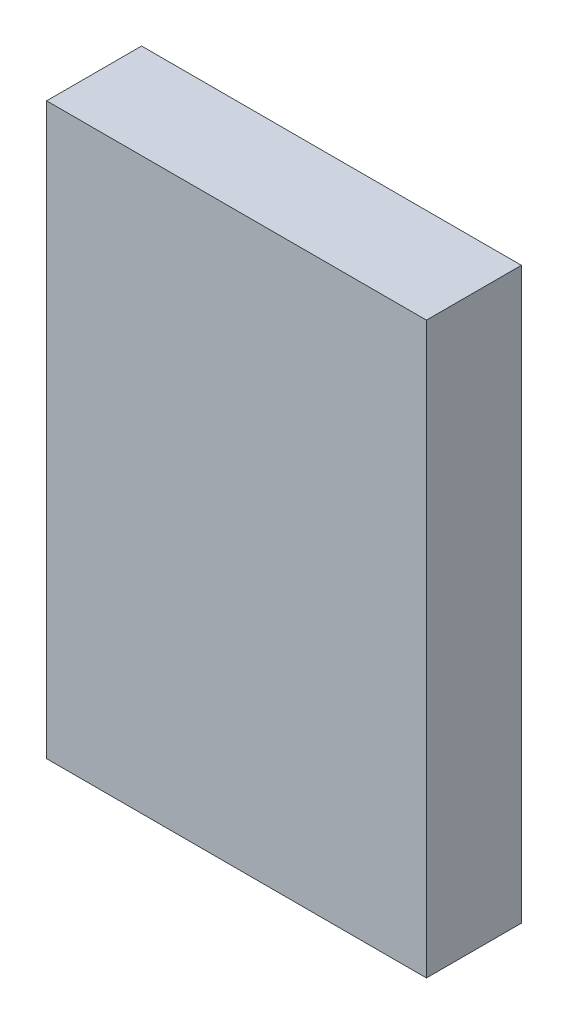
SolidWorks part; units mm, degrees
ref_plane "Plan de face" through (0, 0, 0) normal (0, 0, 1) x (1, 0, 0)
ref_plane "Plan de dessus" through (0, 0, 0) normal (0, 1, 0) x (1, 0, 0)
ref_plane "Plan de droite" through (0, 0, 0) normal (1, 0, 0) x (0, 0, -1)
sketch "Esquisse2" plane through (0, 0, 0) normal (0, 0, 1) x (1, 0, 0)
  line L0 (9.5, -169.7139) -> (7.4697, -182.6334)
  line L1 (9.5, -161.7766) -> (7.4697, -148.8571)
  line L2 (2.5303, -148.8571) -> (0.5, -161.7766)
  line L3 (0.5, -169.7139) -> (2.5303, -182.6334)
  line L7 (-15, -135.7453) -> (25, -135.7453)
  line L8 (-15, -135.7453) -> (-15, -195.7453)
  line L9 (-15, -195.7453) -> (25, -195.7453)
  line L10 (25, -135.7453) -> (25, -195.7453)
  arc A0 (9.5, -161.7766) -> (9.5, -169.7139) centre (5, -165.7453) cw
  arc A1 (0.5, -161.7766) -> (0.5, -169.7139) centre (5, -165.7453) ccw
  arc A2 (7.4697, -148.8571) -> (2.5303, -148.8571) centre (5, -149.2453) ccw
  arc A3 (7.4697, -182.6334) -> (2.5303, -182.6334) centre (5, -182.2453) cw
  dimension "D1" = 2.5
  dimension "D5" = 16.5
  dimension "D6" = 16.5
  dimension "D7" = 2.5
  dimension "D11" = 16.5
  dimension "D12" = 16.5
  dimension "D14" = 6
  dimension "D15" = 6
  dimension "D17" = 20
  dimension "D18" = 20
  dimension "D20" = 30
  dimension "D2" = 13.078
  dimension "D3" = 13.078
  dimension "D4" = 17.862
  dimension "D8" = 17.862
  dimension "D9" = 13.078
  dimension "D10" = 13.078
  dimension "D13" = 60
  dimension "D16" = 40
  dimension "D19" = 30
extrude "Boss.-Extru.1" add sketch "Esquisse2" along normal blind 5
sketch "Esquisse3" plane through (0, 0, 5) normal (0, 0, 1) x (1, 0, 0)
  line L1 (-15, -135.7453) -> (25, -135.7453)
  line L2 (-15, -135.7453) -> (-15, -195.7453)
  line L3 (-15, -195.7453) -> (25, -195.7453)
  line L4 (25, -135.7453) -> (25, -195.7453)
extrude "Boss.-Extru.2" add sketch "Esquisse3" along normal blind 5
